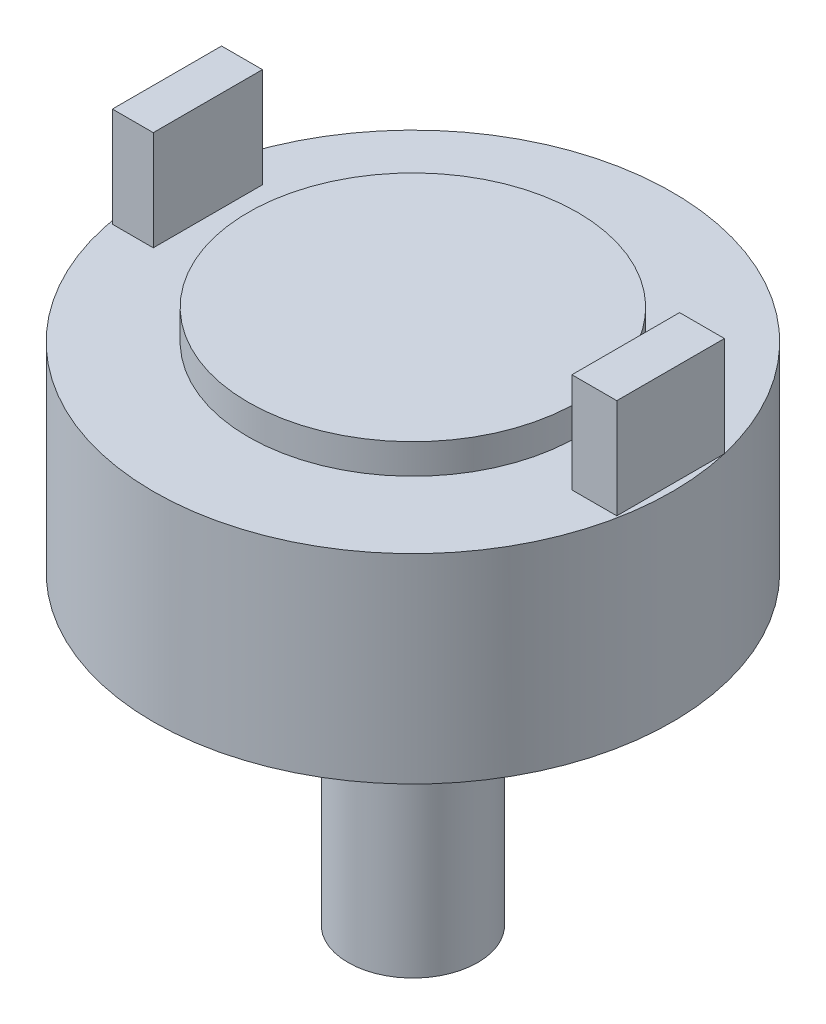
SolidWorks part; units mm, degrees
ref_plane "Front Plane" through (0, 0, 0) normal (0, 0, 1) x (1, 0, 0)
ref_plane "Top Plane" through (0, 0, 0) normal (0, 1, 0) x (1, 0, 0)
ref_plane "Right Plane" through (0, 0, 0) normal (1, 0, 0) x (0, 0, -1)
sketch "Sketch3" plane through (0, 0, 0) normal (0, 1, 0) x (1, 0, 0)
  circle A0 centre (0, 0) radius 26
  circle A1 centre (0, 0) radius 16.5
  dimension "D1" = 52
  dimension "D2" = 33
extrude "Boss-Extrude1" add sketch "Sketch3" along normal blind 20
sketch "Sketch4" plane through (0, 20, 0) normal (0, 1, 0) x (1, 0, 0)
  circle A0 centre (0, 0) radius 16.5
extrude "Boss-Extrude2" add sketch "Sketch4" against normal blind 10.6326 and the other way blind 3 separate body
sketch "Sketch5" plane through (0, 9.3674, 0) normal (0, -1, 0) x (1, 0, 0)
  circle A0 centre (0, 0) radius 6.5
  dimension "D1" = 13
extrude "Boss-Extrude3" add sketch "Sketch5" along normal blind 40
sketch "Sketch6" plane through (0, 20, 0) normal (0, 1, 0) x (1, 0, 0)
  line L0 (-25.2754, 6.0954) -> (-21.1781, 6.0954)
  line L1 (20.8219, 5.9069) -> (25.3201, 5.9069)
  line L2 (20.8219, 5.9069) -> (20.8219, -4.8826)
  line L3 (20.8219, -4.8826) -> (25.3201, -4.8826)
  line L4 (25.3201, 5.9069) -> (25.3201, -4.8826)
  line L5 (-25.2754, 6.0954) -> (-25.2754, -4.8484)
  line L6 (-25.2754, -4.8484) -> (-21.1781, -4.8484)
  line L7 (-21.1781, 6.0954) -> (-21.1781, -4.8484)
  circle A0 centre (0, 0) radius 26 construction
  point P8 (-23.2268, 3.2437)
  point P9 (24.4382, -4.8826)
  point P10 (24.0968, 5.2923)
  point P11 (25.3201, 5.9069)
  point P14 (-25.2754, 6.0954)
  dimension "D1" = 42
extrude "Boss-Extrude4" add sketch "Sketch6" along normal blind 10
